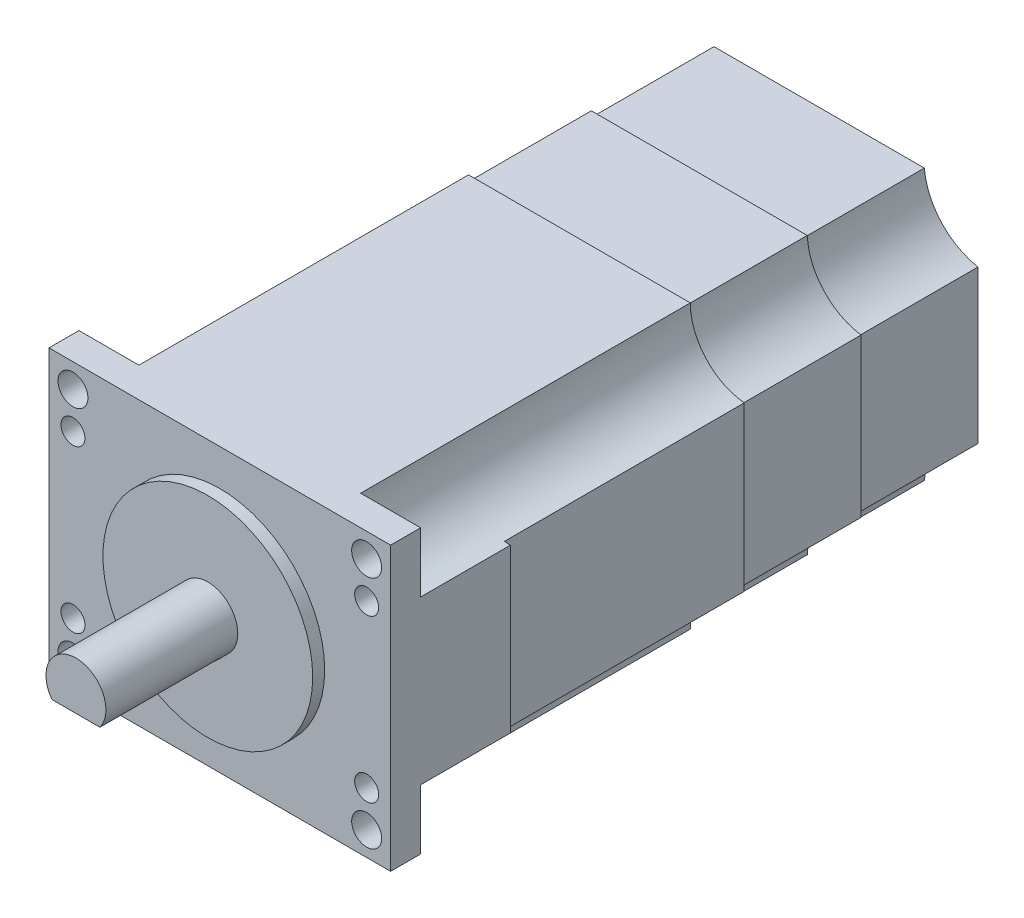
SolidWorks part; units mm, degrees
material "ABS"
ref_plane "前视基准面" through (0, 0, 0) normal (0, 0, 1) x (1, 0, 0)
ref_plane "上视基准面" through (0, 0, 0) normal (0, 1, 0) x (1, 0, 0)
ref_plane "右视基准面" through (0, 0, 0) normal (1, 0, 0) x (0, 0, -1)
other "Configuration Table"
sketch "草图2" plane through (0, 0, 0) normal (0, 0, 1) x (1, 0, 0)
  line L1 (-28.5, 23.57) -> (28.5, 23.57)
  line L2 (-28.5, 23.57) -> (-28.5, -23.57)
  line L3 (-28.5, -23.57) -> (28.5, -23.57)
  line L4 (28.5, 23.57) -> (28.5, -23.57)
  line L5 (-28.5, 23.57) -> (28.5, -23.57) construction
  line L6 (-28.5, -23.57) -> (28.5, 23.57) construction
  point P0 (0, 0)
  dimension "D1" = 57
  dimension "D2" = 47.14
extrude "凸台-拉伸1" add sketch "草图2" along normal blind 100
sketch "草图3" plane through (0, 0, 100) normal (0, 0, 1) x (1, 0, 0)
  circle A0 centre (0, 0) radius 17.5
  dimension "D1" = 35
extrude "凸台-拉伸2" add sketch "草图3" along normal blind 2
sketch "草图4" plane through (0, 0, 102) normal (0, 0, 1) x (1, 0, 0)
  circle A0 centre (0, 0) radius 5
  dimension "D1" = 10
extrude "凸台-拉伸3" add sketch "草图4" along normal blind 22
sketch "草图5" plane through (0, 0, 124) normal (0, 0, 1) x (1, 0, 0)
  line L1 (-7.1811, -3) -> (8.2157, -3)
  line L2 (-7.1811, -3) -> (-7.1811, -8.4771)
  line L3 (-7.1811, -8.4771) -> (8.2157, -8.4771)
  line L4 (8.2157, -3) -> (8.2157, -8.4771)
  circle A0 centre (0, 0) radius 5 construction
  dimension "D1" = 3
extrude "切除-拉伸1" cut sketch "草图5" against normal blind 20
sketch "草图7" plane through (0, 0, 0) normal (0, 0, -1) x (-1, 0, 0)
  line L1 (-28.5, -23.57) -> (-28.5, 23.57) construction
  line L2 (28.5, -23.57) -> (-28.5, -23.57) construction
  circle A0 centre (28.5, 23.57) radius 10
  circle A1 centre (28.5, -23.57) radius 10
  circle A2 centre (-28.5, -23.57) radius 10
  circle A3 centre (-28.5, 23.57) radius 10
  dimension "D1" = 20
extrude "切除-拉伸2" cut sketch "草图7" against normal blind 95
sketch "草图8" plane through (0, 0, 100) normal (0, 0, 1) x (1, 0, 0)
  line L0 (-24.5, 19.57) -> (-24.5, -19.57) construction
  line L1 (-24.5, -19.57) -> (24.5, -19.57) construction
  line L2 (24.5, -19.57) -> (24.5, 19.57) construction
  line L3 (24.5, 19.57) -> (-24.5, 19.57) construction
  line L4 (-28.5, 23.57) -> (-28.5, -23.57) construction
  line L5 (28.5, -23.57) -> (28.5, 23.57) construction
  line L6 (28.5, 23.57) -> (-28.5, 23.57) construction
  line L7 (-28.5, -23.57) -> (28.5, -23.57) construction
  circle A0 centre (-24.5, 19.57) radius 2.5
  circle A1 centre (24.5, 19.57) radius 2.5
  circle A2 centre (24.5, -19.57) radius 2.5
  circle A3 centre (-24.5, -19.57) radius 2.5
  dimension "D1" = 5
  dimension "D2" = 4
  dimension "D3" = 4
  dimension "D4" = 4
  dimension "D5" = 4
extrude "切除-拉伸3" cut sketch "草图8" against normal blind 90
sketch "草图9" plane through (0, 0, 0) normal (0, 0, -1) x (-1, 0, 0)
  line L0 (-18.5, 23.57) -> (-28.5, 23.57) construction
  line L1 (27.5, -23.57) -> (-27.5, -23.57)
  line L2 (27.5, -23.57) -> (27.5, 23.57)
  line L3 (27.5, 23.57) -> (-27.5, 23.57)
  line L4 (-27.5, -23.57) -> (-27.5, 23.57)
  line L5 (27.5, -23.57) -> (-27.5, 23.57) construction
  line L6 (27.5, 23.57) -> (-27.5, -23.57) construction
  line L7 (-28.5, -13.57) -> (-28.5, 13.57) construction
  point P0 (0, 0)
  dimension "D1" = 1
extrude "切除-拉伸4" cut sketch "草图9" against normal blind 80 flip side to cut
sketch "草图10" plane through (0, 0, 0) normal (0, 0, -1) x (-1, 0, 0)
  line L4 (-27.5, 13.6201) -> (-27.5, -13.6201)
  line L5 (-18.5, -23.57) -> (18.5, -23.57)
  line L6 (27.5, -13.6201) -> (27.5, 13.6201)
  line L7 (18.5, 23.57) -> (-18.5, 23.57)
  line L8 (-27.5, 13.6201) -> (-27.5, -13.6201)
  line L9 (-18.5, -23.57) -> (18.5, -23.57)
  line L10 (27.5, -13.6201) -> (27.5, 13.6201)
  line L11 (18.5, 23.57) -> (-18.5, 23.57)
  line L12 (-27, 13.1777) -> (-27, -13.1777)
  line L13 (-18.0119, -23.07) -> (18.0119, -23.07)
  line L14 (27, -13.1777) -> (27, 13.1777)
  line L15 (18.0119, 23.07) -> (-18.0119, 23.07)
  arc A4 (-18.5, -23.57) -> (-27.5, -13.6201) centre (-28.5, -23.57) ccw
  arc A5 (27.5, -13.6201) -> (18.5, -23.57) centre (28.5, -23.57) ccw
  arc A6 (18.5, 23.57) -> (27.5, 13.6201) centre (28.5, 23.57) ccw
  arc A7 (-27.5, 13.6201) -> (-18.5, 23.57) centre (-28.5, 23.57) ccw
  arc A8 (-18.5, -23.57) -> (-27.5, -13.6201) centre (-28.5, -23.57) ccw
  arc A9 (27.5, -13.6201) -> (18.5, -23.57) centre (28.5, -23.57) ccw
  arc A10 (18.5, 23.57) -> (27.5, 13.6201) centre (28.5, 23.57) ccw
  arc A11 (-27.5, 13.6201) -> (-18.5, 23.57) centre (-28.5, 23.57) ccw
  arc A12 (-18.0119, -23.07) -> (-27, -13.1777) centre (-28.5, -23.57) ccw
  arc A13 (27, -13.1777) -> (18.0119, -23.07) centre (28.5, -23.57) ccw
  arc A14 (18.0119, 23.07) -> (27, 13.1777) centre (28.5, 23.57) ccw
  arc A15 (-27, 13.1777) -> (-18.0119, 23.07) centre (-28.5, 23.57) ccw
  dimension "D1" = 0
  dimension "D2" = 0.5
extrude "切除-拉伸5" cut sketch "草图10" against normal blind 40
sketch "草图11" plane through (0, 0, 0) normal (0, 0, -1) x (-1, 0, 0)
  line L4 (-27, 13.1777) -> (-27, -13.1777)
  line L5 (-27, 13.1777) -> (-27, -13.1777)
  line L6 (-18.0119, -23.07) -> (18.0119, -23.07)
  line L7 (-18.0119, -23.07) -> (18.0119, -23.07)
  line L12 (17.5455, 22.57) -> (-17.5455, 22.57)
  line L13 (26.5, -12.7533) -> (26.5, 12.7533)
  line L14 (-17.5455, -22.57) -> (17.5455, -22.57)
  line L15 (-26.5, 12.7533) -> (-26.5, -12.7533)
  line L16 (27, -13.1777) -> (27, 13.1777)
  line L17 (27, -13.1777) -> (27, 13.1777)
  line L18 (18.0119, 23.07) -> (-18.0119, 23.07)
  line L19 (18.0119, 23.07) -> (-18.0119, 23.07)
  arc A4 (-27, 13.1777) -> (-18.0119, 23.07) centre (-28.5, 23.57) ccw
  arc A5 (-27, 13.1777) -> (-18.0119, 23.07) centre (-28.5, 23.57) ccw
  arc A6 (-18.0119, -23.07) -> (-27, -13.1777) centre (-28.5, -23.57) ccw
  arc A7 (-18.0119, -23.07) -> (-27, -13.1777) centre (-28.5, -23.57) ccw
  arc A12 (-26.5, 12.7533) -> (-17.5455, 22.57) centre (-28.5, 23.57) ccw
  arc A13 (17.5455, 22.57) -> (26.5, 12.7533) centre (28.5, 23.57) ccw
  arc A14 (26.5, -12.7533) -> (17.5455, -22.57) centre (28.5, -23.57) ccw
  arc A15 (-17.5455, -22.57) -> (-26.5, -12.7533) centre (-28.5, -23.57) ccw
  arc A16 (27, -13.1777) -> (18.0119, -23.07) centre (28.5, -23.57) ccw
  arc A17 (27, -13.1777) -> (18.0119, -23.07) centre (28.5, -23.57) ccw
  arc A18 (18.0119, 23.07) -> (27, 13.1777) centre (28.5, 23.57) ccw
  arc A19 (18.0119, 23.07) -> (27, 13.1777) centre (28.5, 23.57) ccw
  dimension "D1" = 0
  dimension "D2" = 0.5
extrude "切除-拉伸6" cut sketch "草图11" against normal blind 20
sketch "草图12" plane through (0, 0, 100) normal (0, 0, 1) x (1, 0, 0)
  line L0 (-24.5, -19.57) -> (-24.5, 19.57) construction
  line L1 (-24.5, 13.5) -> (24.5, 13.5) construction
  line L2 (-24.5, 13.5) -> (-24.5, -13.5) construction
  line L3 (-24.5, -13.5) -> (24.5, -13.5) construction
  line L4 (24.5, 13.5) -> (24.5, -13.5) construction
  line L5 (-24.5, 13.5) -> (24.5, -13.5) construction
  line L6 (-24.5, -13.5) -> (24.5, 13.5) construction
  line L7 (24.5, -19.57) -> (24.5, 19.57) construction
  circle A0 centre (-24.5, 13.5) radius 2
  circle A1 centre (-24.5, -13.5) radius 2
  circle A2 centre (24.5, -13.5) radius 2
  circle A3 centre (24.5, 13.5) radius 2
  point P0 (0, 0)
  dimension "D2" = 4
  dimension "D3" = 4
  dimension "D4" = 4
  dimension "D5" = 4
  dimension "D1" = 27
extrude "切除-拉伸7" cut sketch "草图12" against normal blind 4
